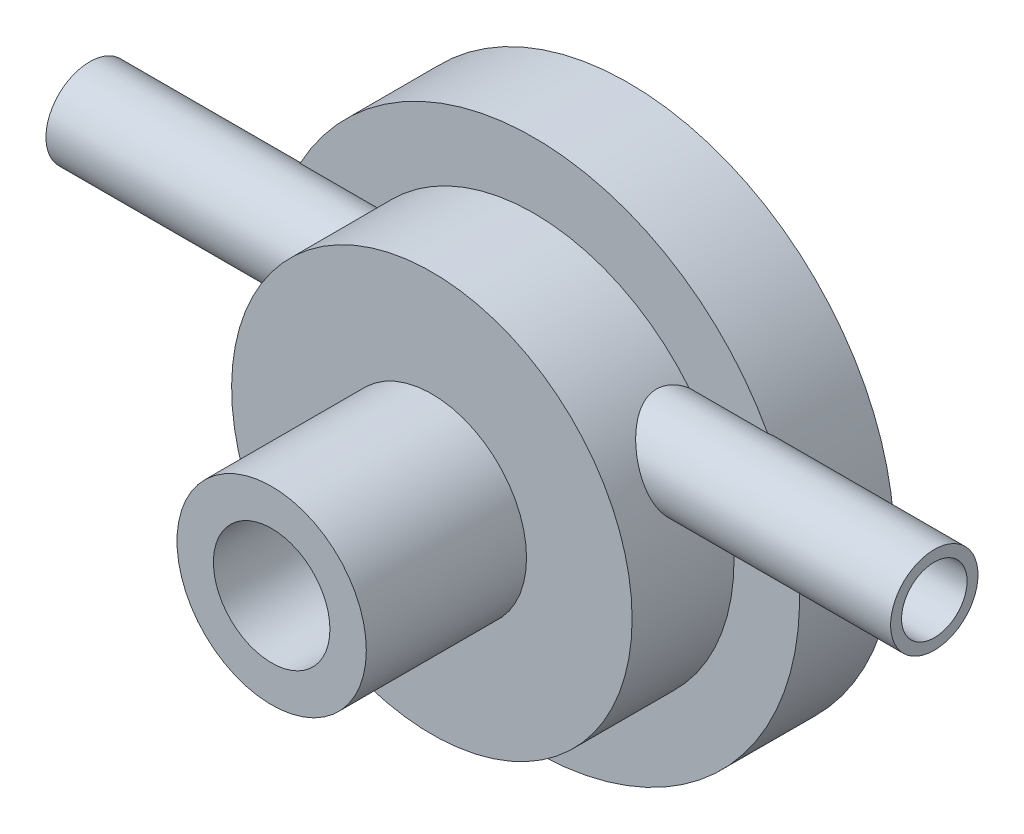
SolidWorks part; units mm, degrees
ref_plane "Front Plane" through (0, 0, 0) normal (0, 0, 1) x (1, 0, 0)
ref_plane "Top Plane" through (0, 0, 0) normal (0, 1, 0) x (1, 0, 0)
ref_plane "Right Plane" through (0, 0, 0) normal (1, 0, 0) x (0, 0, -1)
sketch "Sketch1" plane through (0, 0, 0) normal (0, 0, 1) x (1, 0, 0)
  circle A0 centre (0, 0) radius 36.5
  dimension "D1" = 73
extrude "Boss-Extrude1" add sketch "Sketch1" along normal blind 13
sketch "Sketch2" plane through (0, 0, 13) normal (0, 0, 1) x (1, 0, 0)
  circle A0 centre (0, 0) radius 27.5
  dimension "D1" = 55
extrude "Boss-Extrude2" add sketch "Sketch2" along normal blind 14
sketch "Sketch3" plane through (0, 0, 27) normal (0, 0, 1) x (1, 0, 0)
  circle A0 centre (0, 0) radius 13
  dimension "D1" = 26
extrude "Boss-Extrude3" add sketch "Sketch3" along normal blind 22
sketch "Sketch4" plane through (0, 0, 49) normal (0, 0, 1) x (1, 0, 0)
  circle A0 centre (0, 0) radius 8
  dimension "D1" = 16
extrude "Cut-Extrude1" cut sketch "Sketch4" against normal through all
ref_plane "Plane2" through (36.5, 0, 0) normal (1, 0, 0) x (0, 0, -1)
sketch "Sketch6" plane through (36.5, 0, 0) normal (1, 0, 0) x (0, 0, -1)
  line L0 (0, -36.5) -> (0, 36.5) construction
  line L2 (-13, 27.5) -> (-27, 27.5) construction
  circle A0 centre (-16.5, 12.5) radius 6
  point P4 (0, 0)
  dimension "D1" = 12
  dimension "D2" = 16.5
  dimension "D3" = 15
extrude "Boss-Extrude4" add sketch "Sketch6" along normal blind 22 and the other way blind 94
sketch "Sketch8" plane through (0, 0, 0) normal (0, 0, -1) x (-1, 0, 0)
  ellipse E0 centre (0, 0) end of major axis (22.2412, 0) minor radius 20.0632
extrude "Cut-Extrude2" cut sketch "Sketch8" against normal blind 13
sketch "Sketch10" plane through (58.5, 0, 0) normal (1, 0, 0) x (0, 0, -1)
  circle A0 centre (-16.5, 12.5) radius 4.5
  dimension "D1" = 9
extrude "Cut-Extrude3" cut sketch "Sketch10" against normal through all
